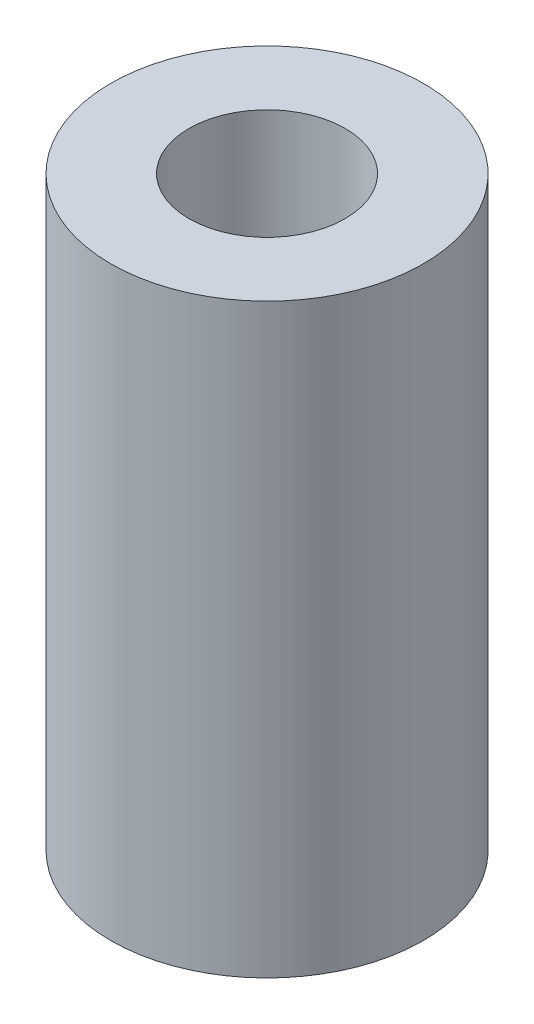
SolidWorks part; units mm, degrees
ref_plane "Front Plane" through (0, 0, 0) normal (0, 0, 1) x (1, 0, 0)
ref_plane "Top Plane" through (0, 0, 0) normal (0, 1, 0) x (1, 0, 0)
ref_plane "Right Plane" through (0, 0, 0) normal (1, 0, 0) x (0, 0, -1)
sketch "Sketch1" plane through (0, 0, 0) normal (0, 1, 0) x (1, 0, 0)
  circle A0 centre (0, 0) radius 4
  dimension "D1" = 8
extrude "Boss-Extrude1" add sketch "Sketch1" along normal blind 15
cosmetic thread "Cosmetic Thread1" parameters "D1"=10, "D2"=6.891
sketch "Sketch2" plane through (0, 15, 0) normal (0, 1, 0) x (1, 0, 0)
  circle A0 centre (0, 0) radius 2
  dimension "D1" = 4
extrude "Cut-Extrude1" cut sketch "Sketch2" against normal up to next contours A0
